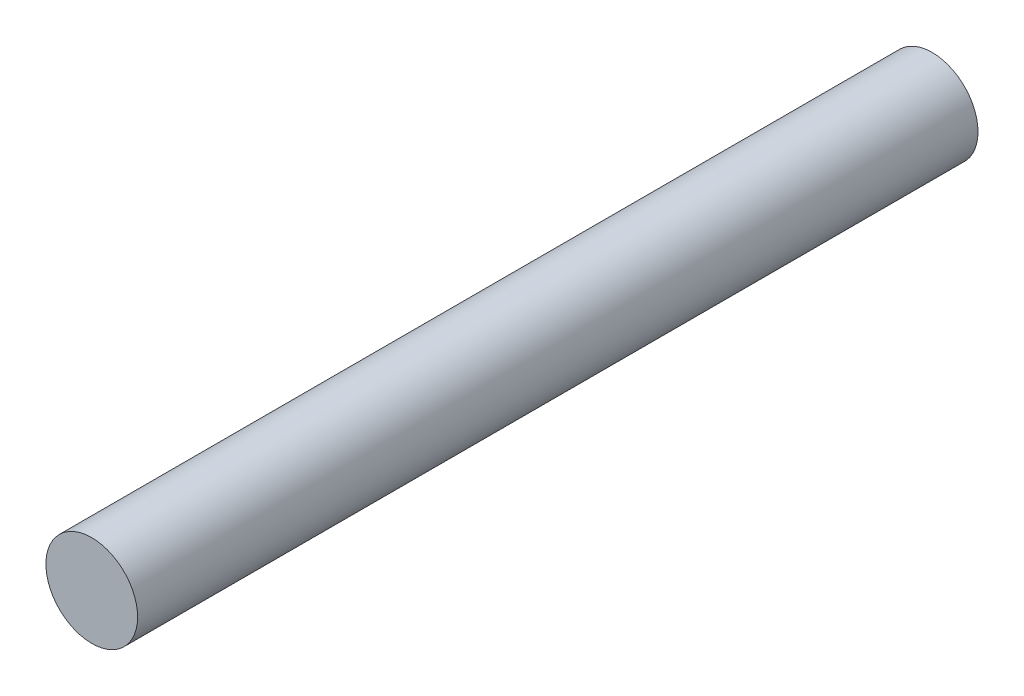
SolidWorks part; units mm, degrees
ref_plane "Front Plane" through (0, 0, 0) normal (0, 0, 1) x (1, 0, 0)
ref_plane "Top Plane" through (0, 0, 0) normal (0, 1, 0) x (1, 0, 0)
ref_plane "Right Plane" through (0, 0, 0) normal (1, 0, 0) x (0, 0, -1)
sketch "Sketch1" plane through (0, 0, 0) normal (0, 0, 1) x (1, 0, 0)
  circle A0 centre (0, 0) radius 2.4
  dimension "D1" = 4.8
extrude "Boss-Extrude1" add sketch "Sketch1" along normal blind 44
